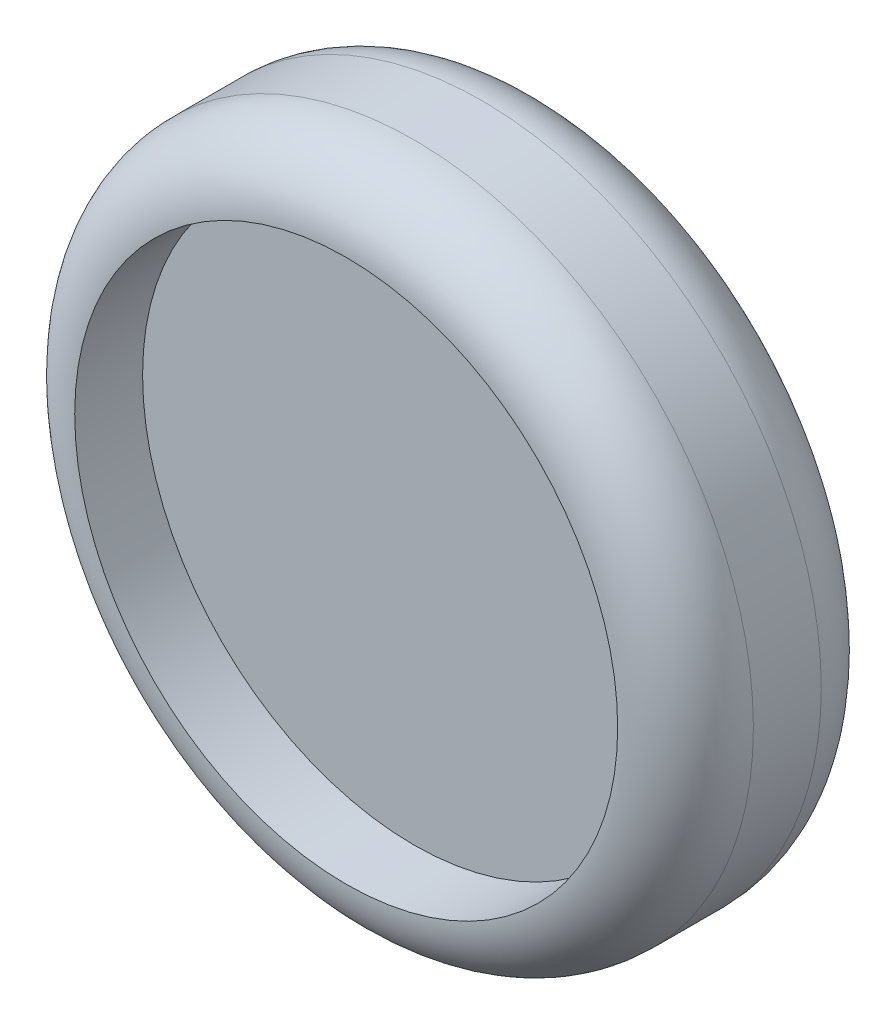
SolidWorks part; units mm, degrees
material "BUTYL"
ref_plane "Front Plane" through (0, 0, 0) normal (0, 0, 1) x (1, 0, 0)
ref_plane "Top Plane" through (0, 0, 0) normal (0, 1, 0) x (1, 0, 0)
ref_plane "Right Plane" through (0, 0, 0) normal (1, 0, 0) x (0, 0, -1)
sketch "Sketch1" plane through (0, 0, 0) normal (0, 0, 1) x (1, 0, 0)
  circle A0 centre (0, 0) radius 50
extrude "Boss-Extrude1" add sketch "Sketch1" along normal blind 30
fillet "Fillet1" radius 10 2 edges at (50, 0, 30) (50, 0, 0)
sketch "Sketch2" plane through (0, 0, 30) normal (0, 0, 1) x (1, 0, 0)
  circle A0 centre (0, 0) radius 40
extrude "Cut-Extrude1" cut sketch "Sketch2" against normal blind 10
sketch "Sketch3" plane through (0, 0, 0) normal (0, 0, -1) x (-1, 0, 0)
  circle A0 centre (0, 0) radius 40
extrude "Cut-Extrude2" cut sketch "Sketch3" against normal blind 10
scale "Scale1" scale about centroid uniform scaling yes scale factor 2
